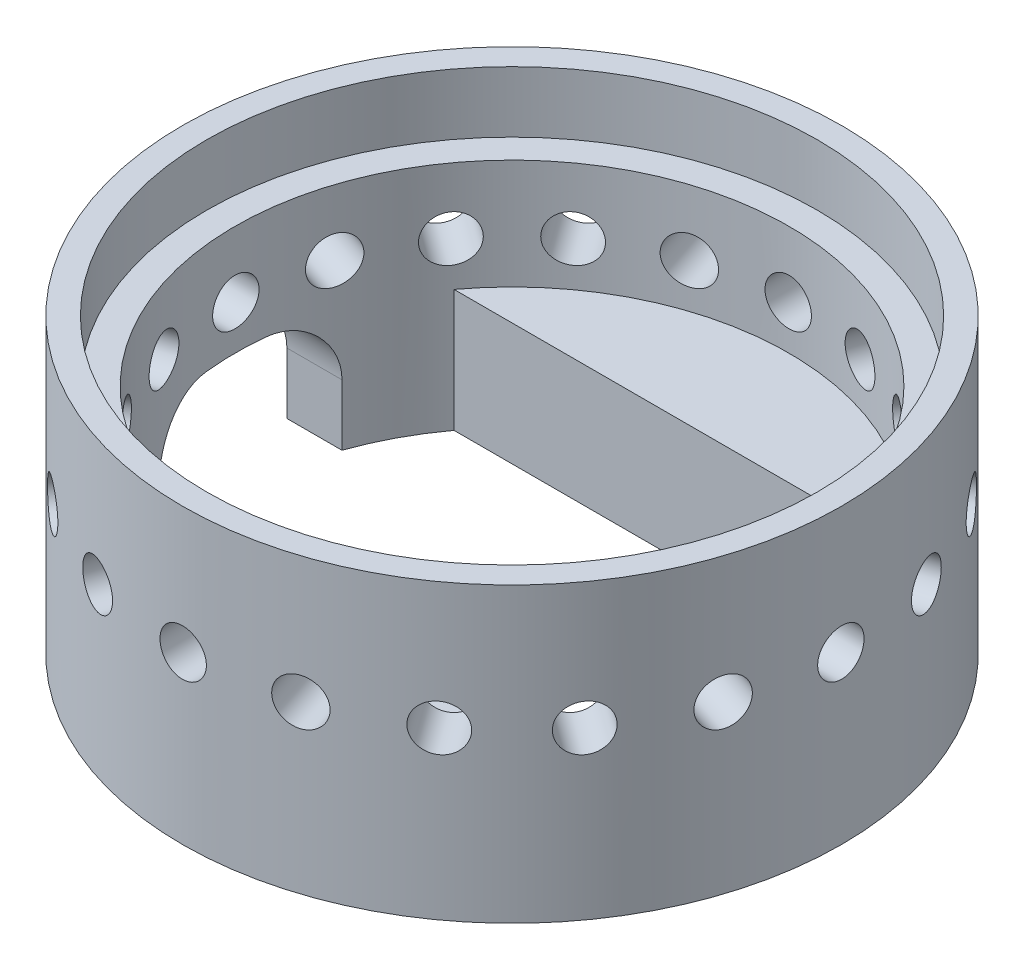
SolidWorks part; units mm, degrees
ref_plane "Front Plane" through (0, 0, 0) normal (0, 0, 1) x (1, 0, 0)
ref_plane "Top Plane" through (0, 0, 0) normal (0, 1, 0) x (1, 0, 0)
ref_plane "Right Plane" through (0, 0, 0) normal (1, 0, 0) x (0, 0, -1)
sketch "Sketch1" plane through (0, 0, 0) normal (0, 1, 0) x (1, 0, 0)
  circle A0 centre (0, 0) radius 22.7
  circle A1 centre (0, 0) radius 25 construction
  circle A2 centre (0, 0) radius 27
  dimension "D1" = 45.4
  dimension "D2" = 50
  dimension "D3" = 2
extrude "Boss-Extrude1" add sketch "Sketch1" along normal blind 24
sketch "Sketch2" plane through (0, 24, 0) normal (0, 1, 0) x (1, 0, 0)
  circle A0 centre (0, 0) radius 25 construction
  circle A1 centre (0, 0) radius 25
extrude "Cut-Extrude1" cut sketch "Sketch2" against normal blind 5
sketch "Sketch3" plane through (0, 0, 0) normal (0, -1, 0) x (1, 0, 0)
  line L0 (22.8715, 0) -> (-22.8715, 0) construction
  line L1 (18.2494, 13.5) -> (-18.2494, 13.5)
  line L2 (18.2494, -13.5) -> (-18.2494, -13.5)
  line L3 (22.8715, -13.5) -> (-22.8715, -13.5) construction
  line L4 (22.8715, 13.5) -> (-22.8715, 13.5) construction
  circle A0 centre (0, 0) radius 22.7 construction
  arc A1 (-18.2494, -13.5) -> (18.2494, -13.5) centre (0, 0) ccw
  arc A2 (18.2494, 13.5) -> (-18.2494, 13.5) centre (0, 0) ccw
  point P4 (0, 0)
  dimension "D1" = 13.5
  dimension "D2" = 13.5
extrude "Boss-Extrude2" add sketch "Sketch3" against normal blind 10
sketch "Sketch4" plane through (0, 0, 0) normal (1, 0, 0) x (0, 0, -1)
  line L0 (7.5, 0) -> (-7.5, 0)
  line L1 (2.5, 10) -> (-2.5, 10)
  line L2 (7.5, 5) -> (7.5, 0)
  line L3 (-7.5, 5) -> (-7.5, 0)
  line L4 (7.5, 10) -> (-7.5, 10) construction
  arc A0 (2.5, 10) -> (7.5, 5) centre (2.5, 5) cw
  arc A1 (-2.5, 10) -> (-7.5, 5) centre (-2.5, 5) ccw
  point P4 (0, 0)
  dimension "D3" = 5
  dimension "D1" = 15
  dimension "D2" = 10
extrude "Cut-Extrude2" cut sketch "Sketch4" against normal through all
ref_plane "Plane1" through (-27, 0, 0) normal (-1, 0, 0) x (0, 0, 1)
sketch "Sketch5" plane through (-27, 0, 0) normal (-1, 0, 0) x (0, 0, 1)
  line L0 (-21.8086, 11.6) -> (21.8086, 11.6) construction
  line L1 (22.7, 19) -> (-22.7, 19) construction
  line L2 (-21.8086, 15.65) -> (21.8086, 15.65) construction
  line L3 (0, 11.6) -> (0, 15.65) construction
  circle A0 centre (0, 13.625) radius 1.9
  point P3 (0, 11.6)
  dimension "D3" = 3.8
  dimension "D1" = 7.4
  dimension "D2" = 4.05
extrude "Cut-Extrude3" cut sketch "Sketch5" against normal up to next
pattern_circular "CirPattern1" count 20 over 360 about axis through (0, 24, 0) along (0, 1, 0) of "Cut-Extrude3"
